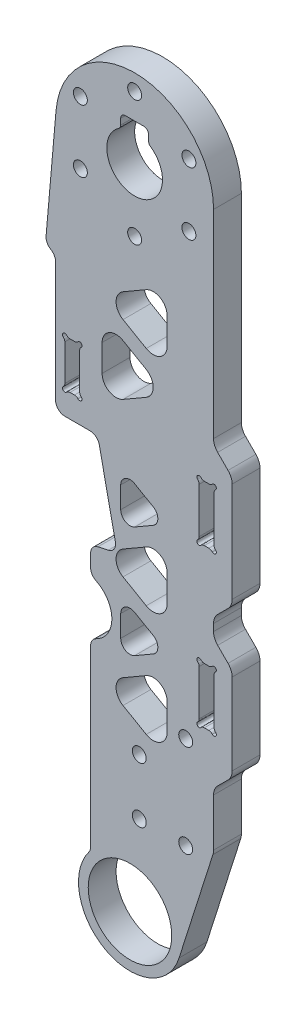
SolidWorks part; units mm, degrees
material "Thornel Mat VMA"
ref_plane "前视基准面" through (0, 0, 0) normal (0, 0, 1) x (1, 0, 0)
ref_plane "上视基准面" through (0, 0, 0) normal (0, 1, 0) x (1, 0, 0)
ref_plane "右视基准面" through (0, 0, 0) normal (1, 0, 0) x (0, 0, -1)
other "Configuration Table"
ref_plane "基准面1" through (0, 0, 0) normal (0, 0, -1) x (-1, 0, 0)
sketch "草图1" plane through (0, 0, 0) normal (0, 0, -1) x (-1, 0, 0)
  line L0 (-2.1075, 35.6677) -> (-1.1436, 35.6677)
  line L1 (-0.0256, 34.5497) -> (-0.0256, 24.7857)
  line L2 (-1.1436, 23.6677) -> (-2.1075, 23.6677)
  line L3 (-3.2256, 24.7857) -> (-3.2256, 34.5497)
  line L4 (10.8744, 93.1163) -> (10.8744, 94.3717)
  line L5 (11.8744, 95.3717) -> (15.8744, 95.3717)
  line L6 (16.8744, 94.3717) -> (16.8744, 93.1163)
  line L7 (11.3744, 65.1525) -> (16.3744, 62.2658)
  line L8 (16.3744, 57.0696) -> (11.3744, 54.1829)
  line L9 (6.8744, 56.7809) -> (6.8744, 62.5544)
  line L10 (6.8744, 8.7809) -> (6.8744, 14.5544)
  line L11 (11.3744, 17.1525) -> (16.3744, 14.2658)
  line L12 (16.3744, 9.0696) -> (11.3744, 6.1829)
  line L13 (13.8744, -4.3738) -> (9.8744, -2.0644)
  line L14 (9.8744, 1.3997) -> (13.8744, 3.7091)
  line L15 (16.8744, 1.9771) -> (16.8744, -2.6417)
  line L16 (6.8744, -15.2191) -> (6.8744, -9.4456)
  line L17 (11.3744, -6.8475) -> (16.3744, -9.7342)
  line L18 (16.3744, -14.9304) -> (11.3744, -17.8171)
  line L19 (9.8744, 25.3997) -> (13.8744, 27.7091)
  line L20 (16.8744, 25.9771) -> (16.8744, 21.3583)
  line L21 (13.8744, 19.6262) -> (9.8744, 21.9356)
  line L22 (20.8744, 50.5544) -> (20.8744, 44.7809)
  line L23 (16.3744, 42.1829) -> (11.3744, 45.0696)
  line L24 (11.3744, 50.2658) -> (16.3744, 53.1525)
  line L25 (-3.2256, -9.2143) -> (-3.2256, 0.5497)
  line L26 (-2.1075, 1.6677) -> (-1.1436, 1.6677)
  line L27 (-0.0256, 0.5497) -> (-0.0256, -9.2143)
  line L28 (-1.1436, -10.3323) -> (-2.1075, -10.3323)
  line L29 (32.9557, 64.3249) -> (30.8097, 88.8533)
  line L30 (-3.1256, 87.3717) -> (-3.1256, 44.6143)
  line L31 (-4.0042, 42.493) -> (-6.2469, 40.2504)
  line L32 (-7.1256, 38.1291) -> (-7.1256, 16.6143)
  line L33 (-6.2469, 14.493) -> (-4.0042, 12.2504)
  line L34 (-3.1256, 10.1291) -> (-3.1256, 8.6143)
  line L35 (-4.0042, 6.493) -> (-6.2469, 4.2504)
  line L36 (-7.1256, 2.1291) -> (-7.1256, -15.3857)
  line L37 (-6.2469, -17.507) -> (-4.0042, -19.7496)
  line L38 (-3.1256, -21.8709) -> (-3.1256, -32.1629)
  line L39 (-2.9845, -33.0719) -> (4.3019, -55.9897)
  line L40 (23.3496, -44.7719) -> (23.3496, -7.1987)
  line L41 (23.3496, 7.2512) -> (23.3496, 10.0239)
  line L42 (21.7655, 11.9802) -> (19.5635, 12.4483)
  line L43 (18.0231, 14.8204) -> (21.5009, 31.1826)
  line L44 (23.4572, 32.7667) -> (28.9071, 32.7667)
  line L45 (30.9071, 34.7667) -> (30.9071, 60.6199)
  line L47 (28.9158, 46.6448) -> (28.9158, 38.8848)
  line L48 (27.7977, 37.7667) -> (26.8338, 37.7667)
  line L49 (25.7158, 38.8848) -> (25.7158, 46.6448)
  line L50 (28.9158, 42.7648) -> (25.7158, 42.7648) construction
  line L51 (27.7977, 47.7628) -> (26.8338, 47.7628)
  arc A0 (-3.2256, 34.5497) -> (-3.5589, 35.295) centre (-4.2256, 34.5497) ccw
  arc A1 (-3.5589, 35.295) -> (-2.8529, 36.001) centre (-3.2256, 35.6677) cw
  arc A2 (-2.8529, 36.001) -> (-2.1075, 35.6677) centre (-2.1075, 36.6677) ccw
  arc A3 (-1.1436, 35.6677) -> (-0.3982, 36.001) centre (-1.1436, 36.6677) ccw
  arc A4 (-0.3982, 36.001) -> (0.3078, 35.295) centre (-0.0256, 35.6677) cw
  arc A5 (0.3078, 35.295) -> (-0.0256, 34.5497) centre (0.9744, 34.5497) ccw
  arc A6 (-0.0256, 24.7857) -> (0.3078, 24.0404) centre (0.9744, 24.7857) ccw
  arc A7 (0.3078, 24.0404) -> (-0.3982, 23.3344) centre (-0.0256, 23.6677) cw
  arc A8 (-0.3982, 23.3344) -> (-1.1436, 23.6677) centre (-1.1436, 22.6677) ccw
  arc A9 (-2.1075, 23.6677) -> (-2.8529, 23.3344) centre (-2.1075, 22.6677) ccw
  arc A10 (-2.8529, 23.3344) -> (-3.5589, 24.0404) centre (-3.2256, 23.6677) cw
  arc A11 (-3.5589, 24.0404) -> (-3.2256, 24.7857) centre (-4.2256, 24.7857) ccw
  circle A12 centre (13.8744, 87.3717) radius 13.5
  circle A13 centre (13.8744, 100.8717) radius 1.5
  circle A14 centre (2.1831, 94.1217) radius 1.5
  circle A15 centre (2.1831, 80.6217) radius 1.5
  circle A16 centre (13.8744, 73.8717) radius 1.5
  circle A17 centre (25.5658, 80.6217) radius 1.5
  arc A18 (16.8744, 93.1163) -> (17.303, 92.2956) centre (17.8744, 93.1163) ccw
  arc A19 (17.303, 92.2956) -> (10.4459, 92.2956) centre (13.8744, 87.3717) cw
  arc A20 (10.4459, 92.2956) -> (10.8744, 93.1163) centre (9.8744, 93.1163) ccw
  arc A21 (10.8744, 94.3717) -> (11.8744, 95.3717) centre (11.8744, 94.3717) cw
  arc A22 (15.8744, 95.3717) -> (16.8744, 94.3717) centre (15.8744, 94.3717) cw
  arc A23 (6.8744, 62.5544) -> (11.3744, 65.1525) centre (9.8744, 62.5544) cw
  arc A24 (16.3744, 62.2658) -> (16.3744, 57.0696) centre (14.8744, 59.6677) cw
  arc A25 (11.3744, 54.1829) -> (6.8744, 56.7809) centre (9.8744, 56.7809) cw
  arc A26 (11.3744, 6.1829) -> (6.8744, 8.7809) centre (9.8744, 8.7809) cw
  arc A27 (6.8744, 14.5544) -> (11.3744, 17.1525) centre (9.8744, 14.5544) cw
  arc A28 (16.3744, 14.2658) -> (16.3744, 9.0696) centre (14.8744, 11.6677) cw
  arc A29 (16.8744, -2.6417) -> (13.8744, -4.3738) centre (14.8744, -2.6417) cw
  arc A30 (9.8744, -2.0644) -> (9.8744, 1.3997) centre (10.8744, -0.3323) cw
  arc A31 (13.8744, 3.7091) -> (16.8744, 1.9771) centre (14.8744, 1.9771) cw
  circle A32 centre (12.8744, -22.3323) radius 1.5
  circle A33 centre (2.8744, -14.3323) radius 1.5
  circle A34 centre (12.8744, -34.3323) radius 1.5
  circle A35 centre (2.8744, -34.3323) radius 1.5
  circle A36 centre (14.8744, -52.6283) radius 9
  arc A37 (11.3744, -17.8171) -> (6.8744, -15.2191) centre (9.8744, -15.2191) cw
  arc A38 (6.8744, -9.4456) -> (11.3744, -6.8475) centre (9.8744, -9.4456) cw
  arc A39 (16.3744, -9.7342) -> (16.3744, -14.9304) centre (14.8744, -12.3323) cw
  arc A40 (9.8744, 21.9356) -> (9.8744, 25.3997) centre (10.8744, 23.6677) cw
  arc A41 (13.8744, 27.7091) -> (16.8744, 25.9771) centre (14.8744, 25.9771) cw
  arc A42 (16.8744, 21.3583) -> (13.8744, 19.6262) centre (14.8744, 21.3583) cw
  arc A43 (16.3744, 53.1525) -> (20.8744, 50.5544) centre (17.8744, 50.5544) cw
  arc A44 (20.8744, 44.7809) -> (16.3744, 42.1829) centre (17.8744, 44.7809) cw
  arc A45 (11.3744, 45.0696) -> (11.3744, 50.2658) centre (12.8744, 47.6677) cw
  arc A46 (-2.1075, -10.3323) -> (-2.8529, -10.6656) centre (-2.1075, -11.3323) ccw
  arc A47 (-2.8529, -10.6656) -> (-3.5589, -9.9596) centre (-3.2256, -10.3323) cw
  arc A48 (-3.5589, -9.9596) -> (-3.2256, -9.2143) centre (-4.2256, -9.2143) ccw
  arc A49 (-3.2256, 0.5497) -> (-3.5589, 1.295) centre (-4.2256, 0.5497) ccw
  arc A50 (-3.5589, 1.295) -> (-2.8529, 2.001) centre (-3.2256, 1.6677) cw
  arc A51 (-2.8529, 2.001) -> (-2.1075, 1.6677) centre (-2.1075, 2.6677) ccw
  arc A52 (-1.1436, 1.6677) -> (-0.3982, 2.001) centre (-1.1436, 2.6677) ccw
  arc A53 (-0.3982, 2.001) -> (0.3078, 1.295) centre (-0.0256, 1.6677) cw
  arc A54 (0.3078, 1.295) -> (-0.0256, 0.5497) centre (0.9744, 0.5497) ccw
  arc A55 (-0.0256, -9.2143) -> (0.3078, -9.9596) centre (0.9744, -9.2143) ccw
  arc A56 (0.3078, -9.9596) -> (-0.3982, -10.6656) centre (-0.0256, -10.3323) cw
  arc A57 (-0.3982, -10.6656) -> (-1.1436, -10.3323) centre (-1.1436, -11.3323) ccw
  arc A58 (30.9071, 60.6199) -> (31.7477, 62.2496) centre (32.9071, 60.6199) cw
  arc A59 (31.7477, 62.2496) -> (32.1487, 62.5398) centre (13.8744, 87.3717) ccw
  arc A60 (32.1487, 62.5398) -> (32.9557, 64.3249) centre (30.9633, 64.1506) ccw
  arc A61 (30.8097, 88.8533) -> (-3.1256, 87.3717) centre (13.8744, 87.3717) ccw
  arc A62 (-3.1256, 44.6143) -> (-4.0042, 42.493) centre (-6.1256, 44.6143) cw
  arc A63 (-6.2469, 40.2504) -> (-7.1256, 38.1291) centre (-4.1256, 38.1291) ccw
  arc A64 (-7.1256, 16.6143) -> (-6.2469, 14.493) centre (-4.1256, 16.6143) ccw
  arc A65 (-4.0042, 12.2504) -> (-3.1256, 10.1291) centre (-6.1256, 10.1291) cw
  arc A66 (-3.1256, 8.6143) -> (-4.0042, 6.493) centre (-6.1256, 8.6143) cw
  arc A67 (-6.2469, 4.2504) -> (-7.1256, 2.1291) centre (-4.1256, 2.1291) ccw
  arc A68 (-7.1256, -15.3857) -> (-6.2469, -17.507) centre (-4.1256, -15.3857) ccw
  arc A69 (-4.0042, -19.7496) -> (-3.1256, -21.8709) centre (-6.1256, -21.8709) cw
  arc A70 (-3.1256, -32.1629) -> (-2.9845, -33.0719) centre (-0.1256, -32.1629) ccw
  arc A71 (4.3019, -55.9897) -> (23.7496, -45.9719) centre (14.8744, -52.6283) ccw
  arc A72 (23.7496, -45.9719) -> (23.3496, -44.7719) centre (25.3496, -44.7719) cw
  arc A73 (23.3496, -7.1987) -> (22.2084, -5.3925) centre (21.3496, -7.1987) ccw
  arc A74 (22.2084, -5.3925) -> (22.2084, 5.4449) centre (24.7848, 0.0262) cw
  arc A75 (22.2084, 5.4449) -> (23.3496, 7.2512) centre (21.3496, 7.2512) ccw
  arc A76 (23.3496, 10.0239) -> (21.7655, 11.9802) centre (21.3496, 10.0239) ccw
  arc A77 (19.5635, 12.4483) -> (18.0231, 14.8204) centre (19.9794, 14.4046) cw
  arc A78 (21.5009, 31.1826) -> (23.4572, 32.7667) centre (23.4572, 30.7667) cw
  arc A79 (28.9071, 32.7667) -> (30.9071, 34.7667) centre (28.9071, 34.7667) ccw
  circle A81 centre (25.5658, 94.1217) radius 1.5
  arc A88 (28.9158, 38.8848) -> (29.2491, 38.1394) centre (29.9158, 38.8848) ccw
  arc A89 (29.2491, 38.1394) -> (28.5431, 37.4334) centre (28.9158, 37.7667) cw
  arc A90 (28.5431, 37.4334) -> (27.7977, 37.7667) centre (27.7977, 36.7667) ccw
  arc A91 (26.8338, 37.7667) -> (26.0884, 37.4334) centre (26.8338, 36.7667) ccw
  arc A92 (26.0884, 37.4334) -> (25.3824, 38.1394) centre (25.7158, 37.7667) cw
  arc A93 (25.3824, 38.1394) -> (25.7158, 38.8848) centre (24.7158, 38.8848) ccw
  arc A94 (25.3824, 47.3901) -> (25.7158, 46.6448) centre (24.7158, 46.6448) cw
  arc A95 (26.0884, 48.0961) -> (25.3824, 47.3901) centre (25.7158, 47.7628) ccw
  arc A96 (26.8338, 47.7628) -> (26.0884, 48.0961) centre (26.8338, 48.7628) cw
  arc A97 (28.5431, 48.0961) -> (27.7977, 47.7628) centre (27.7977, 48.7628) cw
  arc A98 (29.2491, 47.3901) -> (28.5431, 48.0961) centre (28.9158, 47.7628) ccw
  arc A99 (28.9158, 46.6448) -> (29.2491, 47.3901) centre (29.9158, 46.6448) cw
  point P207 (13.8744, 87.3717)
  point P235 (27.3158, 47.7628)
  point P236 (27.3158, 37.7667)
  dimension "D2" = 17
  dimension "D4" = 6
  dimension "D1" = 27
  dimension "D5" = 3
  dimension "D3" = 140
  dimension "D6" = 3.88
  dimension "D7" = 9.9961
  dimension "D8" = 3.2
  dimension "D9" = 1.9914
  dimension "D10" = 5
extrude "凸台-拉伸1" add sketch "草图1" against normal blind 6 contours A81 A12 A13 A14 A15 A16 A17 L5 A22 L6 A18 A19 A20 L4 A21 | L44 A79 L45 A58 A59 A60 L29 A61 L30 A62 L31 A63 L32 A64 L33 A65 L34 A66 L35 A67 L36 A68 L37 A69 L38 A70 L39 A71 A72 L40 A73 A74 A75 L41 A76 L42 A77 L43 A78 A81 A12 A17 A16 A15 A14 A13
